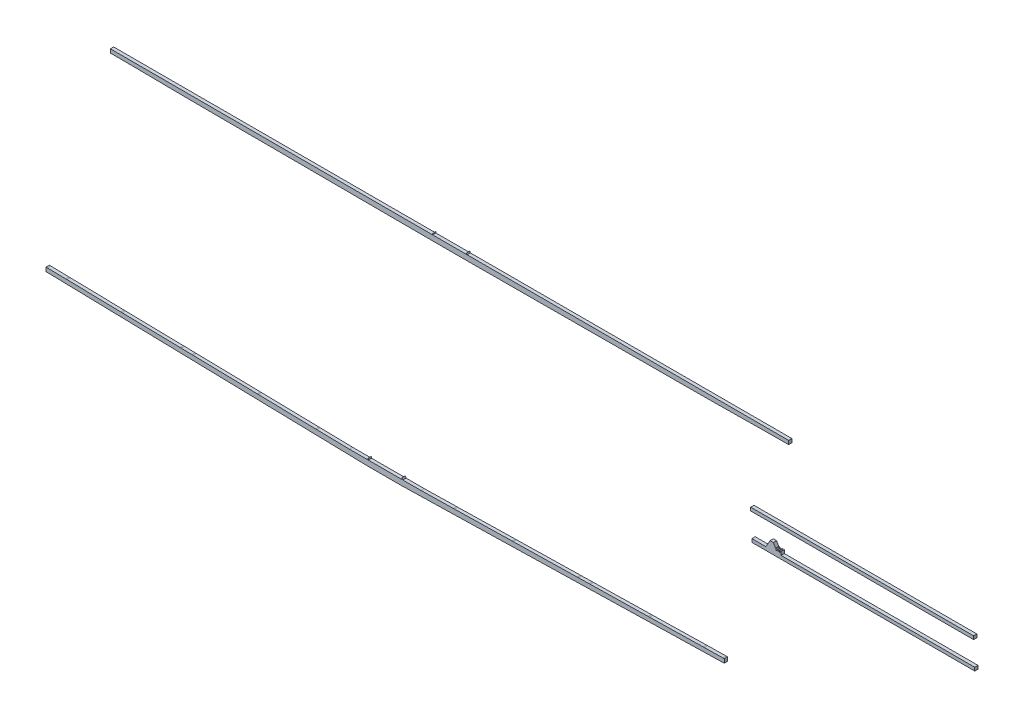
SolidWorks part; units mm, degrees
ref_plane "前视基准面" through (0, 0, 0) normal (0, 0, 1) x (1, 0, 0)
ref_plane "上视基准面" through (0, 0, 0) normal (0, 1, 0) x (1, 0, 0)
ref_plane "右视基准面" through (0, 0, 0) normal (1, 0, 0) x (0, 0, -1)
sketch "Model" plane through (0, 0, 0) normal (0, 0, 1) x (1, 0, 0)
  line L0 (921.8701, 62.105) -> (579.5034, 62.105)
  line L1 (921.8701, 57.005) -> (579.5034, 57.005)
  line L2 (579.5034, 57.005) -> (579.5034, 62.105)
  line L3 (614.2461, 32.4844) -> (617.6765, 26.5428)
  line L4 (581.2813, 21.2098) -> (602.7367, 21.2098)
  line L5 (609.2461, 32.4844) -> (602.7367, 21.2098)
  line L6 (618.5599, 23.568) -> (618.5599, 26.5428)
  line L7 (621.1432, 23.568) -> (621.1432, 26.5428)
  line L8 (621.1432, 26.5428) -> (618.5599, 23.568)
  line L9 (623.7265, 23.568) -> (623.7265, 26.5428)
  line L10 (623.7265, 26.5428) -> (621.1432, 23.568)
  line L11 (623.7265, 23.568) -> (626.1113, 26.5428)
  line L12 (618.5599, 26.5428) -> (617.6765, 26.5428)
  line L13 (581.2813, 16.1098) -> (923.648, 16.1098)
  line L14 (626.1113, 21.2098) -> (923.648, 21.2098)
  line L15 (626.1113, 26.5428) -> (626.1113, 21.2098)
  line L16 (581.2813, 16.1098) -> (581.2813, 21.2098)
  line L17 (921.8701, 62.105) -> (921.8701, 57.005)
  line L18 (923.648, 21.2098) -> (923.648, 16.1098)
  line L19 (609.2461, 32.4844) -> (614.2461, 32.4844)
  line L20 (143.7549, 180.0616) -> (637.7669, 180.0616)
  line L21 (142.7584, 171.9978) -> (221.5172, 172.2628)
  line L22 (221.5172, 172.2628) -> (223.5172, 172.2628)
  line L23 (223.5172, 172.2628) -> (311.5172, 172.5727)
  line L24 (311.5172, 172.5727) -> (313.5172, 172.5727)
  line L25 (313.5172, 172.5727) -> (411.7672, 172.9426)
  line L26 (411.7672, 172.9426) -> (413.7672, 172.9426)
  line L27 (413.7672, 172.9426) -> (429.7672, 172.934)
  line L28 (429.7672, 172.934) -> (431.7672, 172.934)
  line L29 (431.7672, 172.934) -> (520.7532, 173.3198)
  line L30 (520.7532, 173.3198) -> (522.7532, 173.3284)
  line L31 (522.7532, 173.3284) -> (605.4176, 174.2668)
  line L32 (605.4176, 174.2668) -> (607.4176, 174.2668)
  line L33 (635.7669, 174.3895) -> (637.7669, 174.3895)
  line L34 (142.7627, 180.0616) -> (116.7627, 180.0616)
  line L35 (142.7584, 171.9978) -> (116.7627, 171.9978)
  line L36 (142.7627, 180.0616) -> (142.7627, 181.8815)
  line L37 (142.7627, 181.8815) -> (143.7549, 180.0616)
  line L38 (607.4176, 174.2668) -> (635.7669, 174.3895)
  line L39 (637.7669, 180.0616) -> (637.7669, 174.3895)
  line L40 (89.7706, 180.0616) -> (-404.2414, 180.0616)
  line L41 (90.7671, 171.9978) -> (12.0082, 172.2628)
  line L42 (12.0082, 172.2628) -> (10.0082, 172.2628)
  line L43 (10.0082, 172.2628) -> (-77.9918, 172.5727)
  line L44 (-77.9918, 172.5727) -> (-79.9918, 172.5727)
  line L45 (-79.9918, 172.5727) -> (-178.2417, 172.9426)
  line L46 (-178.2417, 172.9426) -> (-180.2417, 172.9426)
  line L47 (-180.2417, 172.9426) -> (-196.2417, 172.934)
  line L48 (-196.2417, 172.934) -> (-198.2417, 172.934)
  line L49 (-198.2417, 172.934) -> (-287.2277, 173.3198)
  line L50 (-287.2277, 173.3198) -> (-289.2277, 173.3284)
  line L51 (-289.2277, 173.3284) -> (-371.8921, 174.2668)
  line L52 (-371.8921, 174.2668) -> (-373.8921, 174.2668)
  line L53 (-402.2414, 174.3895) -> (-404.2414, 174.3895)
  line L54 (90.7627, 180.0616) -> (116.7627, 180.0616)
  line L55 (90.7671, 171.9978) -> (116.7627, 171.9978)
  line L56 (90.7627, 180.0616) -> (90.7627, 181.8815)
  line L57 (90.7627, 181.8815) -> (89.7706, 180.0616)
  line L58 (-373.8921, 174.2668) -> (-402.2414, 174.3895)
  line L59 (-404.2414, 180.0616) -> (-404.2414, 174.3895)
  line L60 (43.8455, -177.4926) -> (538.8103, -165.8562)
  line L61 (43.775, -177.4934) -> (17.8103, -177.4934)
  line L62 (72.9138, -168.9934) -> (122.5606, -168.0091)
  line L63 (421.7966, -162.0486) -> (423.7966, -162.0486)
  line L64 (423.7966, -162.0486) -> (506.4609, -160.2972)
  line L65 (506.4609, -160.2972) -> (508.4609, -160.2972)
  line L66 (536.8103, -159.7762) -> (538.8103, -159.7762)
  line L67 (312.8105, -164.1949) -> (314.8105, -164.1949)
  line L68 (314.8105, -164.1949) -> (330.8105, -163.796)
  line L69 (330.8105, -163.796) -> (332.8105, -163.796)
  line L70 (332.8105, -163.796) -> (421.7966, -162.0486)
  line L71 (212.5914, -166.2048) -> (214.5606, -166.2048)
  line L72 (214.5606, -166.2048) -> (312.8105, -164.1949)
  line L73 (122.5606, -168.0091) -> (124.5606, -168.0091)
  line L74 (124.5606, -168.0091) -> (212.5299, -166.2054)
  line L75 (17.8103, -168.9934) -> (43.775, -168.9934)
  line L76 (43.7803, -166.4905) -> (45.0434, -168.9934)
  line L77 (43.7803, -166.4905) -> (43.775, -168.9934)
  line L78 (45.0434, -168.9934) -> (72.9138, -168.9934)
  line L79 (508.4609, -160.2972) -> (536.8103, -159.7762)
  line L80 (538.8103, -159.7762) -> (538.8103, -165.8562)
  line L81 (-8.225, -177.4926) -> (-503.1897, -165.8562)
  line L82 (-8.1545, -177.4934) -> (17.8103, -177.4934)
  line L83 (-37.2933, -168.9934) -> (-86.9401, -168.0091)
  line L84 (-386.1761, -162.0486) -> (-388.1761, -162.0486)
  line L85 (-388.1761, -162.0486) -> (-470.8404, -160.2972)
  line L86 (-470.8404, -160.2972) -> (-472.8404, -160.2972)
  line L87 (-501.1897, -159.7762) -> (-503.1897, -159.7762)
  line L88 (-277.19, -164.1949) -> (-279.19, -164.1949)
  line L89 (-279.19, -164.1949) -> (-295.19, -163.796)
  line L90 (-295.19, -163.796) -> (-297.19, -163.796)
  line L91 (-297.19, -163.796) -> (-386.1761, -162.0486)
  line L92 (-176.9708, -166.2048) -> (-178.9401, -166.2048)
  line L93 (-178.9401, -166.2048) -> (-277.19, -164.1949)
  line L94 (-86.9401, -168.0091) -> (-88.9401, -168.0091)
  line L95 (-88.9401, -168.0091) -> (-176.9093, -166.2054)
  line L96 (17.8103, -168.9934) -> (-8.1545, -168.9934)
  line L97 (-8.1597, -166.4905) -> (-9.4229, -168.9934)
  line L98 (-8.1597, -166.4905) -> (-8.1545, -168.9934)
  line L99 (-9.4229, -168.9934) -> (-37.2933, -168.9934)
  line L100 (-472.8404, -160.2972) -> (-501.1897, -159.7762)
  line L101 (-503.1897, -159.7762) -> (-503.1897, -165.8562)
  arc A0 (43.775, -177.4934) -> (43.8455, -177.4926) centre (43.775, -174.4934) ccw
  arc A1 (212.5914, -166.2048) -> (212.5299, -166.2054) centre (212.5914, -169.2048) ccw
  arc A2 (-8.225, -177.4926) -> (-8.1545, -177.4934) centre (-8.1545, -174.4934) ccw
  arc A3 (-176.9093, -166.2054) -> (-176.9708, -166.2048) centre (-176.9708, -169.2048) ccw
extrude "凸台-拉伸1" add sketch "Model" along normal blind 5
